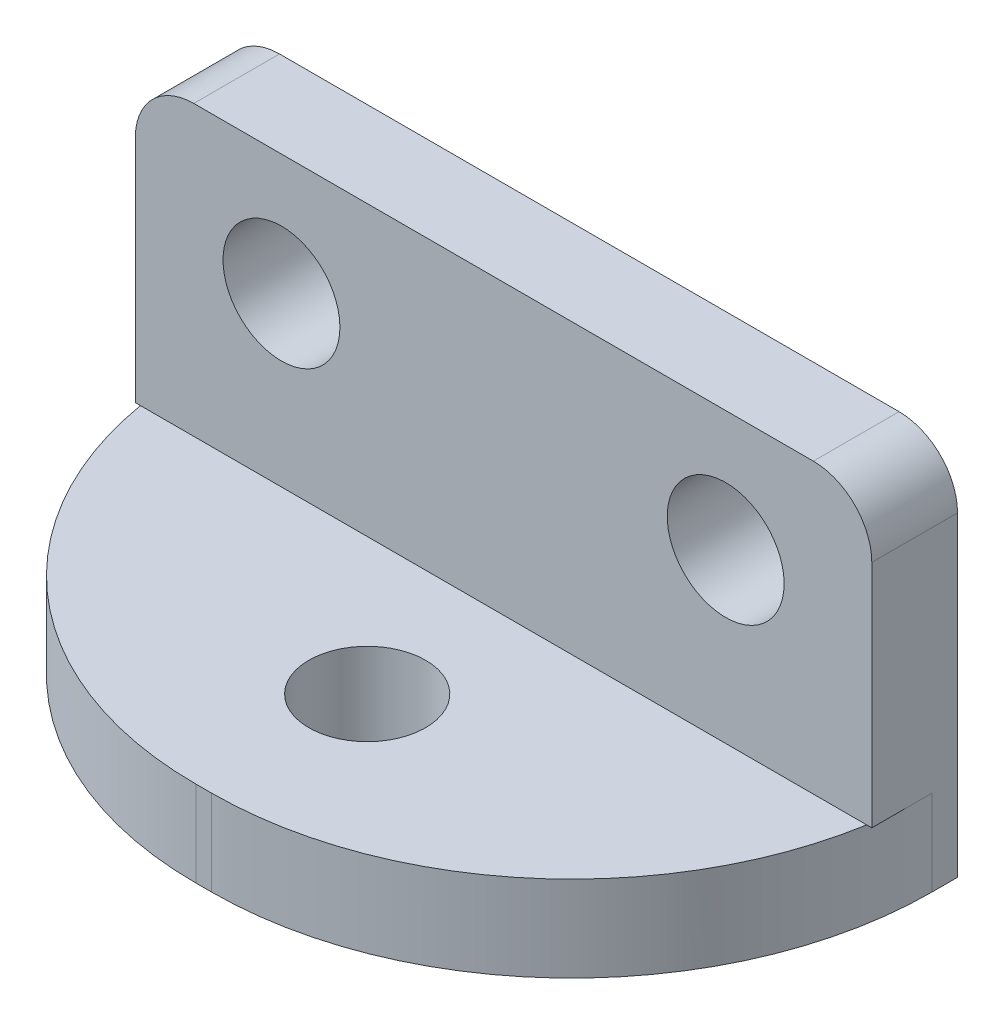
SolidWorks part; units mm, degrees
ref_plane "Front Plane" through (0, 0, 0) normal (0, 0, 1) x (1, 0, 0)
ref_plane "Top Plane" through (0, 0, 0) normal (0, 1, 0) x (1, 0, 0)
ref_plane "Right Plane" through (0, 0, 0) normal (1, 0, 0) x (0, 0, -1)
sketch "Sketch1" plane through (0, 0, 0) normal (0, 0, 1) x (1, 0, 0)
  line L1 (0, 0) -> (18.9, 0)
  line L2 (55, 0) -> (-55, 0) construction
  line L3 (0, 0) -> (0, 8.1)
  line L4 (0, -55) -> (0, 55) construction
  line L5 (18.9, 0) -> (18.9, 8.1)
  line L6 (1.5, 9.6) -> (17.4, 9.6)
  line L7 (3.75, 6.5) -> (17.1296, 6.5) construction
  circle A0 centre (3.75, 6.5) radius 1.5
  circle A1 centre (15.15, 6.5) radius 1.5
  arc A2 (18.9, 8.1) -> (17.4, 9.6) centre (17.4, 8.1) ccw
  arc A3 (0, 8.1) -> (1.5, 9.6) centre (1.5, 8.1) cw
  point P16 (18.9, 9.6)
  point P19 (0, 9.6)
  dimension "D1" = 3.75
  dimension "D5" = 3.75
  dimension "D6" = 1.5
  dimension "D2" = 18.9
  dimension "D3" = 9.6
  dimension "D4" = 3.1
extrude "Boss-Extrude1" add sketch "Sketch1" along normal blind 2.2
sketch "Sketch2" plane through (0, 0, 2.2) normal (0, 0, 1) x (1, 0, 0)
  line L0 (18.9, 0) -> (18.9, 8.1) construction
  line L1 (0, 0) -> (18.9, 0)
  line L2 (0, 0) -> (0, 2.2)
  line L3 (0, 2.2) -> (18.9, 2.2)
  line L4 (18.9, 0) -> (18.9, 2.2)
  dimension "D1" = 2.2
extrude "Boss-Extrude2" add sketch "Sketch2" along normal blind 7.7
sketch "Sketch3" plane through (0, 0, 0) normal (0, -1, 0) x (1, 0, 0)
  line L0 (0, 0.65) -> (0, 9.9)
  line L1 (9.65, 9.9) -> (9.25, 9.9)
  line L2 (18.9, 0.65) -> (18.9, 0)
  line L4 (0, 0.65) -> (0, 0)
  line L5 (0, 9.9) -> (18.9, 9.9) construction
  line L6 (0, 9.9) -> (9.25, 9.9)
  line L7 (9.65, 9.9) -> (18.9, 9.9)
  line L8 (18.9, 9.9) -> (18.9, 0.65)
  line L9 (9.45, 9.9) -> (9.45, 0) construction
  line L10 (0, 0) -> (18.9, 0) construction
  arc A0 (9.65, 9.9) -> (18.9, 0.65) centre (9.65, 0.65) cw
  arc A1 (9.25, 9.9) -> (0, 0.65) centre (9.25, 0.65) ccw
  circle A2 centre (9.45, 5.7) radius 1.5
  point P8 (18.9, 9.9)
  line M8 (18.9, 0) -> (18.9, 9.9)
  line M9 (18.9, 9.9) -> (0, 9.9)
  line M10 (0, 9.9) -> (0, 0)
  dimension "D1" = 9.25
  dimension "D2" = 4.2
extrude "Cut-Extrude1" cut sketch "Sketch3" against normal blind 2.2 contours A1 M9 M10 | A0 M9 M8 | A2
